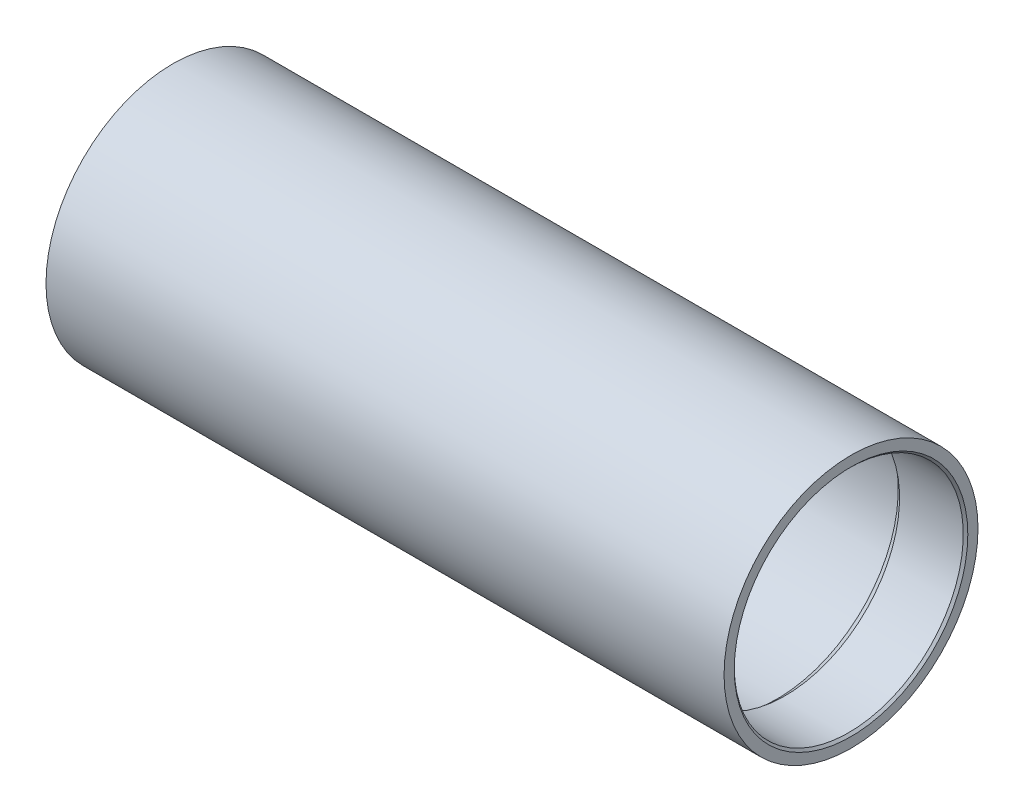
SolidWorks part; units mm, degrees
material "6061-T6 (SS)"
ref_plane "Front Plane" through (0, 0, 0) normal (0, 0, 1) x (1, 0, 0)
ref_plane "Top Plane" through (0, 0, 0) normal (0, 1, 0) x (1, 0, 0)
ref_plane "Right Plane" through (0, 0, 0) normal (1, 0, 0) x (0, 0, -1)
sketch "Sketch1" plane through (0, 0, 0) normal (0, 0, 1) x (1, 0, 0)
  line L0 (0, 55.8) -> (298, 55.8)
  line L1 (0, 0) -> (298, 0) construction
  line L2 (0, 55.8) -> (0, 50.325)
  line L3 (0, 50.325) -> (29, 50.325)
  line L4 (29, 50.325) -> (32.4978, 53.26)
  line L5 (32.4978, 53.26) -> (133.8066, 53.26)
  line L6 (133.8066, 53.26) -> (136.5, 51)
  line L7 (136.5, 51) -> (161.5, 51)
  line L8 (161.5, 51) -> (163.3964, 53.26)
  line L9 (163.3964, 53.26) -> (265.5022, 53.26)
  line L10 (265.5022, 53.26) -> (269, 50.325)
  line L11 (269, 50.325) -> (298, 50.325)
  line L12 (298, 50.325) -> (298, 55.8)
  dimension "D1" = 298
  dimension "D2" = 55.8
  dimension "D3" = 29
  dimension "D4" = 50.325
  dimension "D5" = 107.5
  dimension "D6" = 140
  dimension "D7" = 2.54
  dimension "D8" = 140
  dimension "D9" = 25
  dimension "D10" = 50.325
  dimension "D11" = 2.54
  dimension "D12" = 29
  dimension "D13" = 51
revolve "Revolve1" add sketch "Sketch1" angle 360 about L1
chamfer "Chamfer1" distance 1 angle 45 2 edges at (298, 0, 50.325) (0, 0, 50.325)
